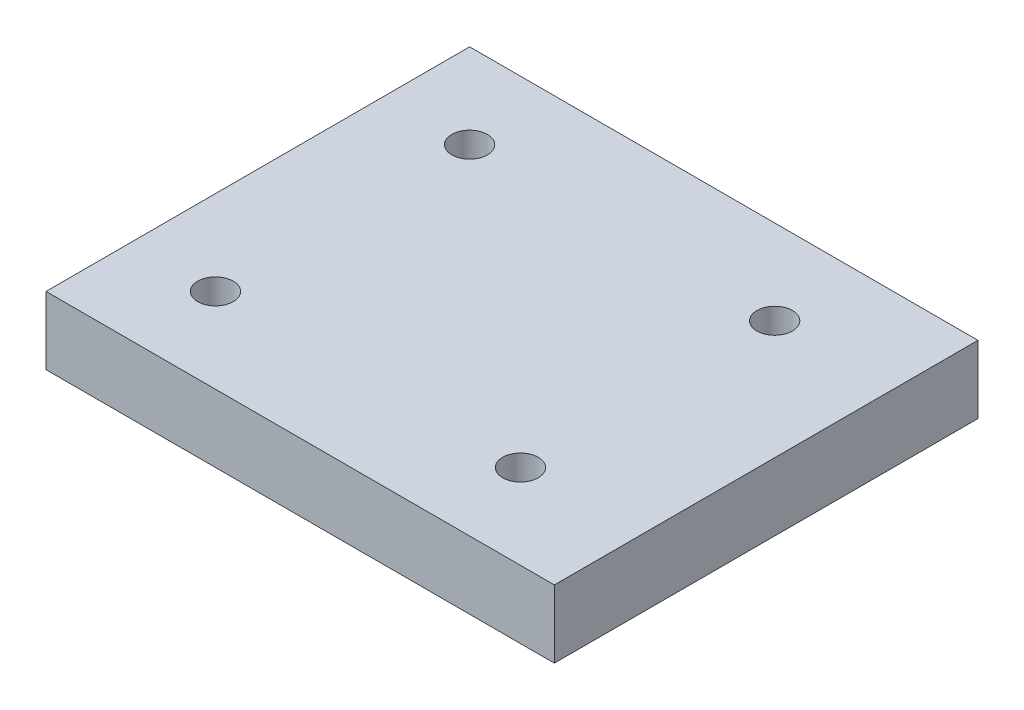
SolidWorks part; units mm, degrees
ref_plane "Front Plane" through (0, 0, 0) normal (0, 0, 1) x (1, 0, 0)
ref_plane "Top Plane" through (0, 0, 0) normal (0, 1, 0) x (1, 0, 0)
ref_plane "Right Plane" through (0, 0, 0) normal (1, 0, 0) x (0, 0, -1)
sketch "Sketch1" plane through (0, 0, 0) normal (0, 1, 0) x (1, 0, 0)
  line L1 (-30, 25) -> (30, 25)
  line L2 (-30, 25) -> (-30, -25)
  line L3 (-30, -25) -> (30, -25)
  line L4 (30, 25) -> (30, -25)
  line L5 (-30, 25) -> (30, -25) construction
  line L6 (-30, -25) -> (30, 25) construction
  point P0 (0, 0)
  dimension "D1" = 50
  dimension "D2" = 60
extrude "Boss-Extrude1" add sketch "Sketch1" along normal blind 8
hole_wizard "M5 Tapped Hole1" positions "Sketch2" profile "Sketch3" tap size "M5" standard "ISO" end condition through all
sketch "Sketch2" plane through (0, 8, 0) normal (0, 1, 0) x (1, 0, 0)
  line L0 (0, 0) -> (-30, 0) construction
  line L1 (-30, 25) -> (-30, -25) construction
  point P0 (-20, -15)
  point P2 (16, -15)
  point P17 (0, 0)
  point P18 (16, 15)
  point P19 (-20, 15)
  dimension "D1" = 20
  dimension "D2" = 36
  dimension "D3" = 15
sketch "Sketch3" plane through (-20, 8, 15) normal (1, 0, 0) x (0, 0, 1)
  line L0 (0, 0) -> (0, 8)
  line L1 (0, 8) -> (2.1, 8)
  line L2 (2.1, 8) -> (2.1, 0)
  line L5 (2.1, 0) -> (0, 0)
  line L11 (0, -6.35) -> (0, 107.95) construction
  dimension "Thru Tap Drill Dia." = 4.2
  dimension "Thru Tap Drill Depth" = 8
cosmetic thread "Hole Thread1"
cosmetic thread "Hole Thread2"
cosmetic thread "Hole Thread3"
cosmetic thread "Hole Thread4"
